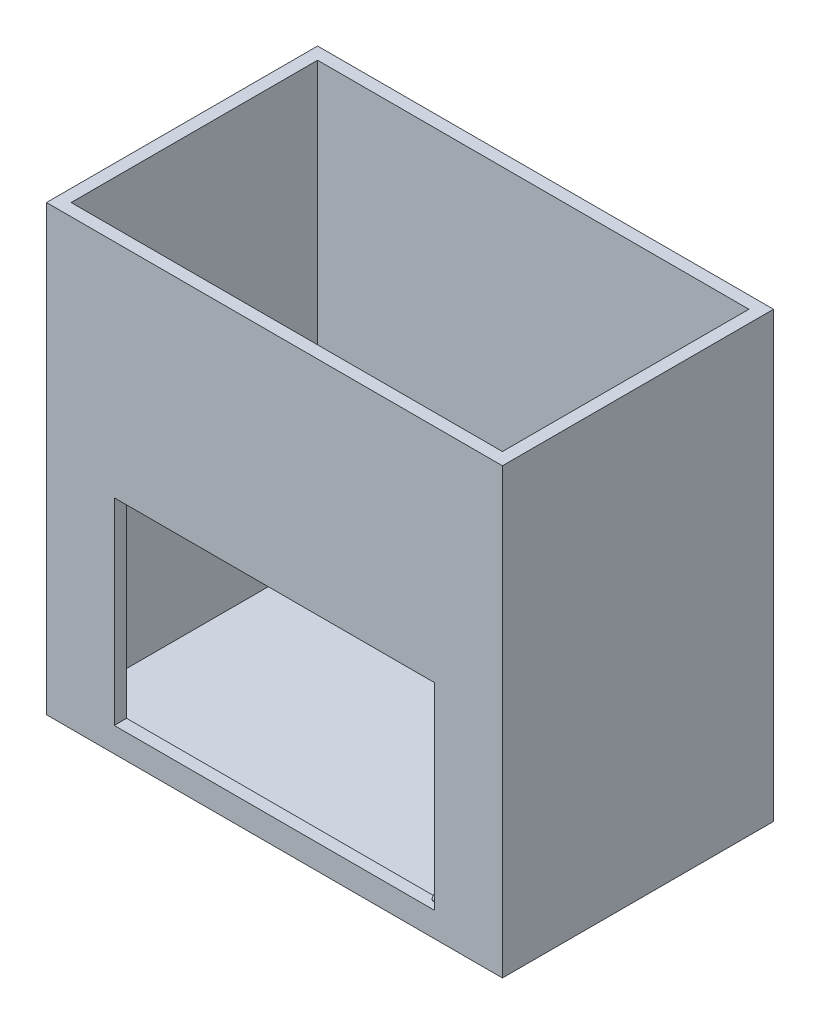
SolidWorks part; units mm, degrees
ref_plane "Front Plane" through (0, 0, 0) normal (0, 0, 1) x (1, 0, 0)
ref_plane "Top Plane" through (0, 0, 0) normal (0, 1, 0) x (1, 0, 0)
ref_plane "Right Plane" through (0, 0, 0) normal (1, 0, 0) x (0, 0, -1)
sketch "Sketch1" plane through (0, 0, 0) normal (0, 1, 0) x (1, 0, 0)
  line L1 (-87.5, 50) -> (87.5, 50)
  line L2 (-87.5, 50) -> (-87.5, -50)
  line L3 (-87.5, -50) -> (87.5, -50)
  line L4 (87.5, 50) -> (87.5, -50)
  line L5 (-87.5, 50) -> (87.5, -50) construction
  line L6 (-87.5, -50) -> (87.5, 50) construction
  point P0 (0, 0)
  dimension "D1" = 100
  dimension "D2" = 175
extrude "Extrude-Thin1" add sketch "Sketch1" along normal blind 175 thin thin type one direction wall 5
sketch "Sketch2" plane through (0, 0, 0) normal (0, -1, 0) x (1, 0, 0)
  line L2 (-92.5, 55) -> (92.5, 55)
  line L3 (-92.5, 55) -> (-92.5, -55)
  line L4 (-92.5, -55) -> (92.5, -55)
  line L5 (92.5, 55) -> (92.5, -55)
extrude "Boss-Extrude2" add sketch "Sketch2" along normal blind 5
sketch "Sketch5" plane through (0, 0, 55) normal (0, 0, 1) x (1, 0, 0)
  line L0 (92.5, -5) -> (-92.5, -5) construction
  line L1 (-65, 85) -> (65, 85)
  line L2 (-65, 85) -> (-65, 5)
  line L3 (-65, 5) -> (65, 5)
  line L4 (65, 85) -> (65, 5)
  line L5 (92.5, -5) -> (-92.5, -5)
  point P8 (0, 5)
  point P9 (0, -5)
  dimension "D1" = 130
  dimension "D2" = 80
  dimension "D3" = 10
extrude "Cut-Extrude2" cut sketch "Sketch5" against normal up to next contours L1 L4 L3 L2
sketch "Sketch6" plane through (65, 0, 0) normal (-1, 0, 0) x (0, 0, 1)
  line L0 (50, 5) -> (55, 5) construction
  line L1 (50, 5) -> (55, 5)
  circle A0 centre (52.5, 7.5) radius 1.5
  point P5 (52.5, 5)
  dimension "D2" = 3
  dimension "D1" = 2.5
extrude "Boss-Extrude3" add sketch "Sketch6" along normal blind 2 contours A0
equation "\"Depth\" = 100"
equation "\"D1@Sketch1\"=\"Depth\""
equation "\"Width\" = 175"
equation "\"D2@Sketch1\"=\"Width\""
equation "\"Height\" = 175"
equation "\"D1@Extrude-Thin1\"=\"Height\""
equation "\"D5@Extrude-Thin1\" = \"Thick\""
equation "\"D1@Boss-Extrude2\"= \"Thick\""
equation "\"Thick\" = 5"
equation "\"D1\" = \"Height\""
